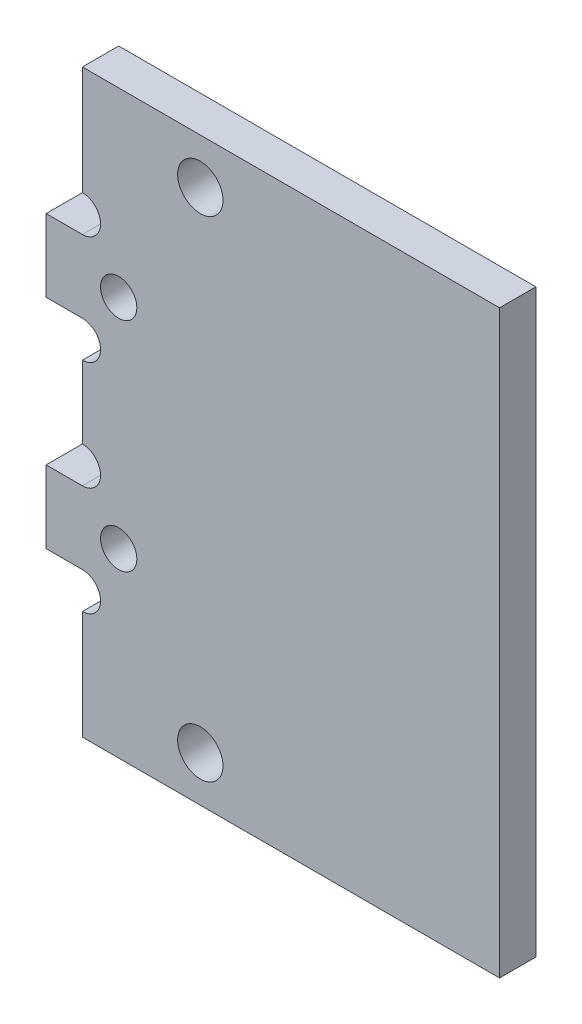
SolidWorks part; units mm, degrees
material "自訂玻璃纖維"
ref_plane "前基準面" through (0, 0, 0) normal (0, 0, 1) x (1, 0, 0)
ref_plane "上基準面" through (0, 0, 0) normal (0, 1, 0) x (1, 0, 0)
ref_plane "右基準面" through (0, 0, 0) normal (1, 0, 0) x (0, 0, -1)
sketch "草圖1" plane through (0, 0, 0) normal (0, 0, 1) x (1, 0, 0)
  line L0 (-17.2162, 10.1625) -> (13.2838, 10.1625)
  line L1 (13.2838, 10.1625) -> (13.2838, -21.8375)
  line L2 (13.2838, -21.8375) -> (-17.2162, -21.8375)
  line L3 (-25.7162, 2.1625) -> (-27.7162, 2.1625)
  line L4 (-27.7162, 2.1625) -> (-27.7162, -1.8375)
  line L5 (-17.2162, 10.1625) -> (-21.7162, 10.1625)
  line L6 (-27.7162, -1.8375) -> (-25.7162, -1.8375)
  line L7 (-17.2162, -21.8375) -> (-19.7162, -21.8375)
  line L8 (-25.7162, -3.8375) -> (-25.7162, -7.8375)
  line L9 (-21.7162, 10.1625) -> (-25.7162, 10.1625)
  line L10 (-27.7162, -9.8375) -> (-27.7162, -13.8375)
  line L11 (-19.7162, -21.8375) -> (-25.7162, -21.8375)
  line L12 (-25.7162, 10.1625) -> (-25.7162, 4.1625)
  line L13 (-25.7162, -9.8375) -> (-27.7162, -9.8375)
  line L14 (-27.7162, -13.8375) -> (-25.7162, -13.8375)
  line L15 (-25.7162, -15.8375) -> (-25.7162, -21.8375)
  circle A0 centre (-19.2162, 7.6625) radius 1.25
  circle A1 centre (-19.2162, -19.3375) radius 1.25
  circle A2 centre (10.7838, -19.3375) radius 1.25
  circle A3 centre (10.7838, 7.6625) radius 1.25
  circle A4 centre (-23.7162, -11.8375) radius 1
  circle A5 centre (-23.7162, 0.1625) radius 1
  arc A6 (-25.7162, 2.1625) -> (-25.7162, 4.1625) centre (-25.7162, 3.1625) ccw
  arc A7 (-25.7162, -1.8375) -> (-25.7162, -3.8375) centre (-25.7162, -2.8375) cw
  arc A8 (-25.7162, -9.8375) -> (-25.7162, -7.8375) centre (-25.7162, -8.8375) ccw
  arc A9 (-25.7162, -13.8375) -> (-25.7162, -15.8375) centre (-25.7162, -14.8375) cw
  dimension "D7" = 4
  dimension "D8" = 4
  dimension "D9" = 2
  dimension "D10" = 2
  dimension "D12" = 2
  dimension "D13" = 2
  dimension "D4" = 2.5
  dimension "D5" = 30
  dimension "D6" = 12
  dimension "D14" = 30
  dimension "D2" = 2.5
  dimension "D3" = 35
  dimension "D11" = 4
extrude "填料-伸長1" add sketch "草圖1" along normal blind 2
sketch "草圖4" plane through (0, 0, 0) normal (0, 0, -1) x (-1, 0, 0)
  line L0 (-13.2838, 5.1625) -> (2.2162, 5.1625)
  line L1 (-13.2838, -21.8375) -> (-13.2838, 10.1625) construction
  line L2 (2.2162, 5.1625) -> (2.2162, -16.8375)
  line L3 (2.2162, -16.8375) -> (-13.2838, -16.8375)
  line L4 (-13.2838, -16.8375) -> (-13.2838, 5.1625)
  circle A0 centre (-10.7838, 7.6625) radius 1.25 construction
  circle A1 centre (-10.7838, -19.3375) radius 1.25 construction
  dimension "D1" = 2.5
  dimension "D2" = 2.5
  dimension "D3" = 15.5
extrude "除料-伸長1" cut sketch "草圖4" against normal blind 2
fillet "圓角2" radius 2.5 2 edges at (13.2838, -16.8375, 1) (13.2838, 5.1625, 1)
fillet "圓角3" radius 5 2 edges at (-2.2162, -16.8375, 1) (-2.2162, 5.1625, 1)
sketch "草圖6" plane through (0, 0, 0) normal (0, 0, -1) x (-1, 0, 0)
  line L0 (-13.2838, 10.1625) -> (25.7162, 10.1625) construction
  line L1 (2.7162, 10.1625) -> (-13.2838, 10.1625)
  line L2 (2.7162, 10.1625) -> (2.7162, -21.8375)
  line L3 (2.7162, -21.8375) -> (-13.2838, -21.8375)
  line L4 (-13.2838, 10.1625) -> (-13.2838, -21.8375)
extrude "除料-伸長3" cut sketch "草圖6" against normal blind 10
